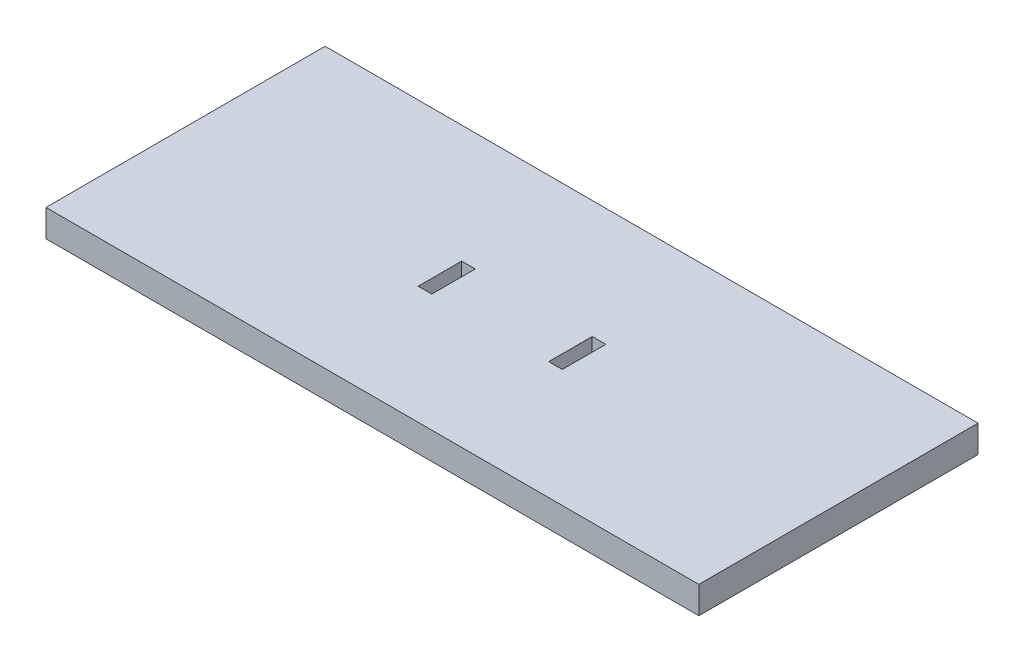
SolidWorks part; units mm, degrees
ref_plane "Front Plane" through (0, 0, 0) normal (0, 0, 1) x (1, 0, 0)
ref_plane "Top Plane" through (0, 0, 0) normal (0, 1, 0) x (1, 0, 0)
ref_plane "Right Plane" through (0, 0, 0) normal (1, 0, 0) x (0, 0, -1)
sketch "Sketch1" plane through (0, 0, 0) normal (0, 1, 0) x (1, 0, 0)
  line L0 (0, 17.2968) -> (0, -11.9819) construction
  line L1 (-60, 25.6535) -> (60, 25.6535)
  line L2 (-60, 25.6535) -> (-60, -25.6535)
  line L3 (-60, -25.6535) -> (60, -25.6535)
  line L4 (60, 25.6535) -> (60, -25.6535)
  line L5 (-60, 25.6535) -> (60, -25.6535) construction
  line L6 (-60, -25.6535) -> (60, 25.6535) construction
  line L7 (-13.25, 4) -> (-10.75, 4)
  line L8 (-13.25, 4) -> (-13.25, -4)
  line L9 (-13.25, -4) -> (-10.75, -4)
  line L10 (-10.75, 4) -> (-10.75, -4)
  line L11 (-13.25, 4) -> (-10.75, -4) construction
  line L12 (-13.25, -4) -> (-10.75, 4) construction
  line L13 (13.25, -4) -> (10.75, -4)
  line L14 (10.75, 4) -> (10.75, -4)
  line L15 (13.25, 4) -> (13.25, -4)
  line L16 (13.25, 4) -> (10.75, -4) construction
  line L17 (13.25, -4) -> (10.75, 4) construction
  line L18 (13.25, 4) -> (10.75, 4)
  point P0 (0, 0)
  point P6 (-12, 0)
  dimension "D1" = 120
  dimension "D2" = 51.307
  dimension "D3" = 2.5
  dimension "D4" = 8
  dimension "D5" = 0
  dimension "D6" = 10.75
extrude "Boss-Extrude2" add sketch "Sketch1" along normal blind 5
